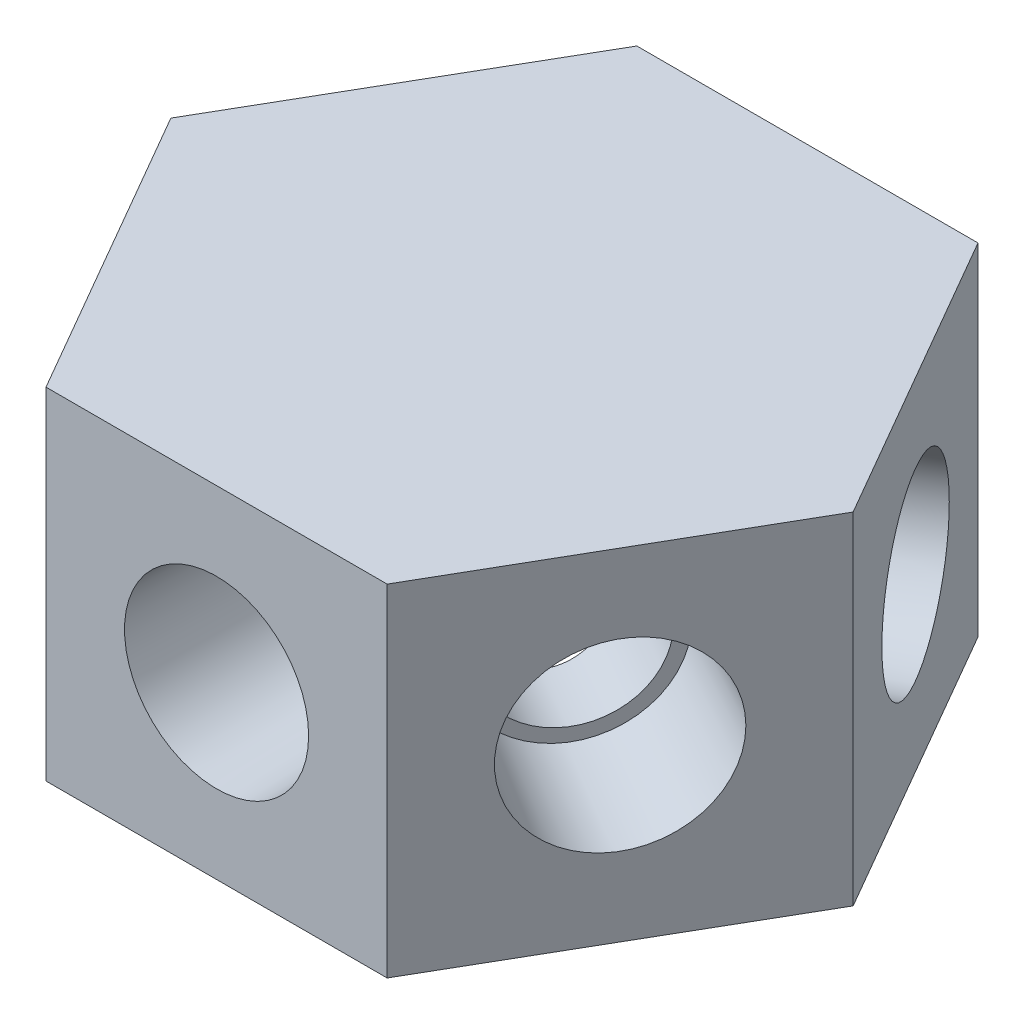
SolidWorks part; units mm, degrees
ref_plane "Front Plane" through (0, 0, 0) normal (0, 0, 1) x (1, 0, 0)
ref_plane "Top Plane" through (0, 0, 0) normal (0, 1, 0) x (1, 0, 0)
ref_plane "Right Plane" through (0, 0, 0) normal (1, 0, 0) x (0, 0, -1)
sketch "Sketch1" plane through (0, 0, 0) normal (0, 1, 0) x (1, 0, 0)
  line L1 (25.4, 0) -> (12.7, 21.997)
  line L2 (12.7, 21.997) -> (-12.7, 21.997)
  line L3 (-12.7, 21.997) -> (-25.4, 0)
  line L4 (-25.4, 0) -> (-12.7, -21.997)
  line L5 (-12.7, -21.997) -> (12.7, -21.997)
  line L6 (12.7, -21.997) -> (25.4, 0)
  circle A0 centre (0, 0) radius 21.997 construction
  dimension "D1" = 25.4
extrude "Boss-Extrude1" add sketch "Sketch1" along normal blind 25.4
hole_wizard "1/4 NPT Tapped Hole1" positions "Sketch3" profile "Sketch2" size "1/4" standard "ANSI Inch"
sketch "Sketch3" plane through (0, 0, 0) normal (0, -1, 0) x (-1, 0, 0)
  point P0 (0, 0)
sketch "Sketch2" plane through (0, 0, 0) normal (1, 0, 0) x (0, 0, -1)
  line L0 (0, 0) -> (0, 20.3603)
  line L1 (5.5626, 17.018) -> (0, 20.3603)
  line L2 (-5.5626, 17.018) -> (0, 20.3603) construction
  line L3 (5.5626, 17.018) -> (5.5626, 9.906)
  line L4 (5.5626, 9.906) -> (6.558, 9.906)
  line L5 (6.558, 9.906) -> (6.8546, 0)
  line L6 (-6.558, 9.906) -> (-6.8546, 0) construction
  line L7 (6.8546, 0) -> (0, 0)
  line L8 (0, -6.35) -> (0, 107.95) construction
  line L11 (-5.5626, 9.906) -> (-6.558, 9.906) construction
  dimension "Tap Drill Dia." = 11.1252
  dimension "Tap Drill Depth" = 17.018
  dimension "Thread Dia." = 13.7092
  dimension "Thread Angle" = 3.43
  dimension "Thread Depth" = 9.906
  dimension "Drill Angle" = 118
hole_wizard "1/4 NPT Tapped Hole2" positions "Sketch5" profile "Sketch4" size "1/4" standard "ANSI Inch"
sketch "Sketch5" plane through (0, 0, 21.997) normal (0, 0, 1) x (1, 0, 0)
  line L0 (0, 0) -> (0, 25.4) construction
  line L1 (-12.7, 0) -> (12.7, 0) construction
  line L2 (-12.7, 25.4) -> (12.7, 25.4) construction
  point P0 (0, 12.7)
sketch "Sketch4" plane through (0, 12.7, 21.997) normal (1, 0, 0) x (0, -1, 0)
  line L0 (0, 0) -> (0, 20.3603)
  line L1 (5.5626, 17.018) -> (0, 20.3603)
  line L2 (-5.5626, 17.018) -> (0, 20.3603) construction
  line L3 (5.5626, 17.018) -> (5.5626, 9.906)
  line L4 (5.5626, 9.906) -> (6.558, 9.906)
  line L5 (6.558, 9.906) -> (6.8546, 0)
  line L6 (-6.558, 9.906) -> (-6.8546, 0) construction
  line L7 (6.8546, 0) -> (0, 0)
  line L8 (0, -6.35) -> (0, 107.95) construction
  line L11 (-5.5626, 9.906) -> (-6.558, 9.906) construction
  dimension "Tap Drill Dia." = 11.1252
  dimension "Tap Drill Depth" = 17.018
  dimension "Thread Dia." = 13.7092
  dimension "Thread Angle" = 3.43
  dimension "Thread Depth" = 9.906
  dimension "Drill Angle" = 118
pattern_circular "CirPattern1" count 6 over 360 about axis through (0, 0, 0) along (0, 1, 0) of "1/4 NPT Tapped Hole2"
